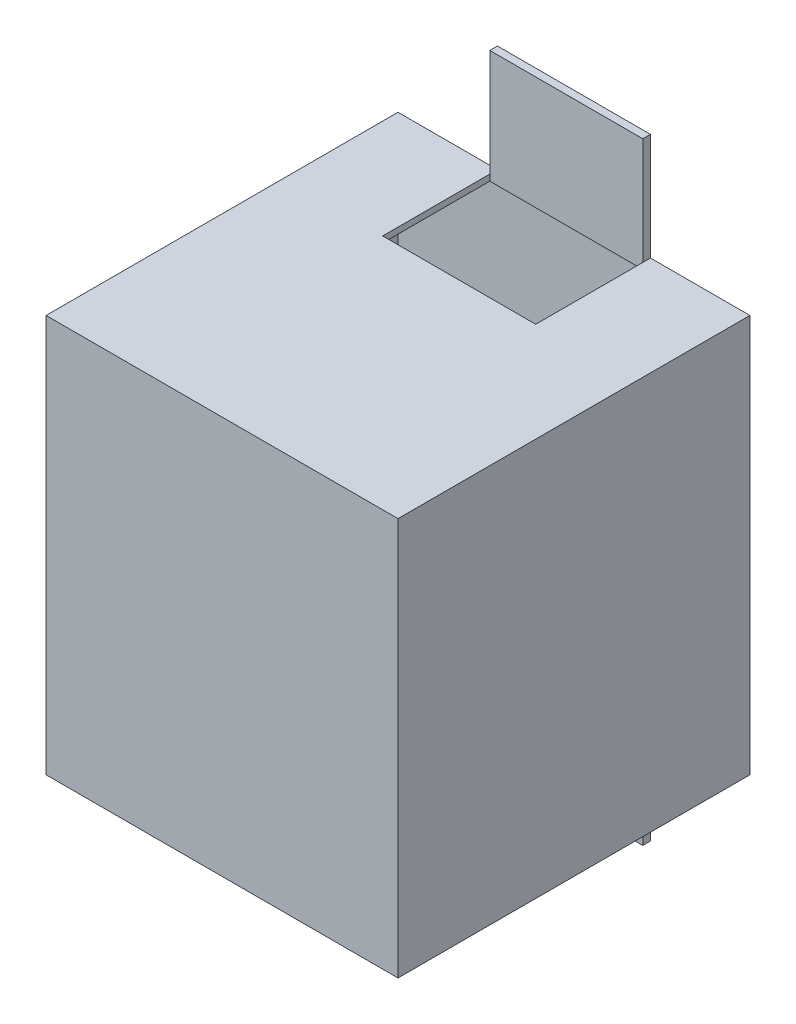
SolidWorks part; units mm, degrees
ref_plane "Plan de face" through (0, 0, 0) normal (0, 0, 1) x (1, 0, 0)
ref_plane "Plan de dessus" through (0, 0, 0) normal (0, 1, 0) x (1, 0, 0)
ref_plane "Plan de droite" through (0, 0, 0) normal (1, 0, 0) x (0, 0, -1)
sketch "Esquisse1" plane through (0, 0, 0) normal (0, 0, 1) x (1, 0, 0)
  line L1 (0, 0) -> (230, 0)
  line L2 (0, 0) -> (0, -260)
  line L3 (0, -260) -> (230, -260)
  line L4 (230, 0) -> (230, -260)
  dimension "D1" = 230
  dimension "D2" = 260
extrude "Boss.-Extru.1" add sketch "Esquisse1" along normal blind 230
sketch "Esquisse2" plane through (0, -260, 0) normal (0, -1, 0) x (1, 0, 0)
  line L0 (0, 230) -> (230, 230) construction
  line L1 (226, 4) -> (4, 4)
  line L2 (226, 4) -> (226, 226)
  line L3 (226, 226) -> (4, 226)
  line L4 (4, 4) -> (4, 226)
  line L5 (0, 230) -> (0, 0) construction
  line L6 (0, 0) -> (230, 0) construction
  line L7 (230, 230) -> (230, 0) construction
  dimension "D1" = 4
  dimension "D2" = 4
  dimension "D3" = 4
  dimension "D4" = 4
extrude "Enlèv. mat.-Extru.1" cut sketch "Esquisse2" against normal blind 256
sketch "Esquisse3" plane through (0, -260, 0) normal (0, -1, 0) x (1, 0, 0)
  line L1 (0, 230) -> (230, 230)
  line L2 (0, 230) -> (0, 0)
  line L3 (0, 0) -> (230, 0)
  line L4 (230, 230) -> (230, 0)
extrude "Boss.-Extru.2" add sketch "Esquisse3" against normal blind 4
sketch "Esquisse4" plane through (0, -260, 0) normal (0, -1, 0) x (1, 0, 0)
  line L0 (0, 230) -> (0, 0) construction
  line L1 (65, 75) -> (165, 75)
  line L2 (65, 75) -> (65, 5)
  line L3 (65, 5) -> (165, 5)
  line L4 (165, 75) -> (165, 5)
  line L5 (230, 230) -> (230, 0) construction
  line L6 (0, 0) -> (230, 0) construction
  dimension "D1" = 70
  dimension "D2" = 100
  dimension "D3" = 65
  dimension "D4" = 65
  dimension "D5" = 5
extrude "Enlèv. mat.-Extru.2" cut sketch "Esquisse4" against normal blind 456
sketch "Esquisse5" plane through (0, -260, 0) normal (0, -1, 0) x (1, 0, 0)
  line L0 (0, 0) -> (230, 0) construction
  line L1 (165, 0) -> (65, 0)
  line L2 (165, 0) -> (165, 5)
  line L3 (165, 5) -> (65, 5)
  line L4 (65, 0) -> (65, 5)
extrude "Boss.-Extru.3" add sketch "Esquisse5" along normal blind 70
sketch "Esquisse6" plane through (0, 0, 0) normal (0, 1, 0) x (1, 0, 0)
  line L0 (230, 0) -> (0, 0) construction
  line L1 (165, -5) -> (65, -5)
  line L2 (165, -5) -> (165, 0)
  line L3 (165, 0) -> (65, 0)
  line L4 (65, -5) -> (65, 0)
extrude "Boss.-Extru.4" add sketch "Esquisse6" along normal blind 70
